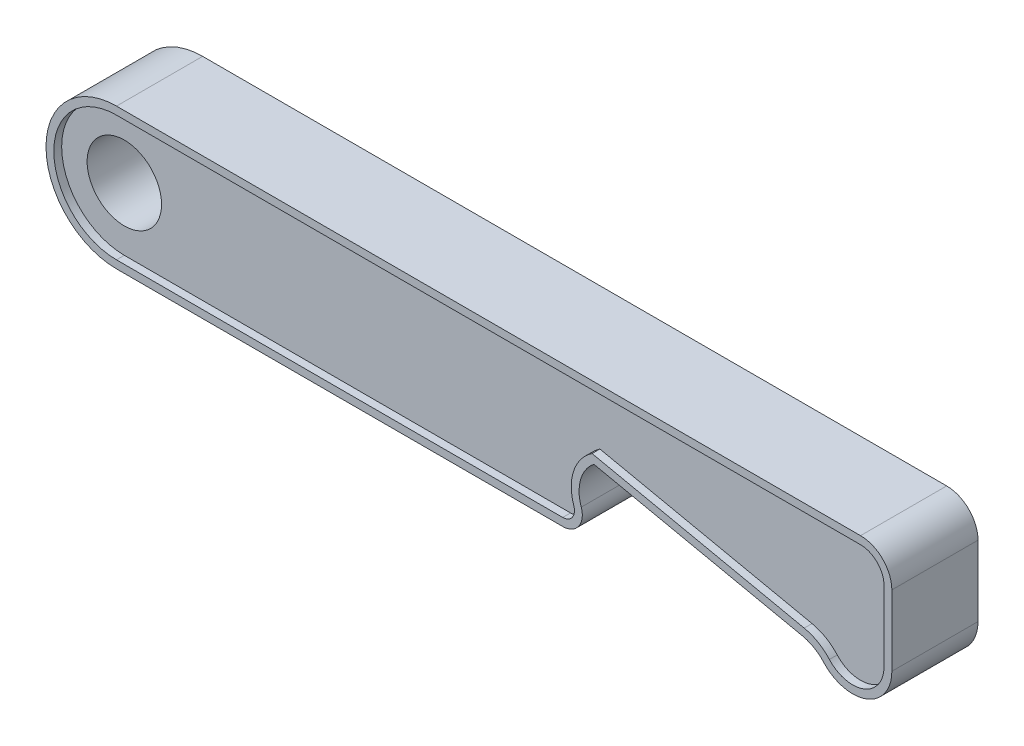
SolidWorks part; units mm, degrees
material "AISI 1015 Steel, Cold Drawn (SS)"
ref_plane "Front Plane" through (0, 0, 0) normal (0, 0, 1) x (1, 0, 0)
ref_plane "Top Plane" through (0, 0, 0) normal (0, 1, 0) x (1, 0, 0)
ref_plane "Right Plane" through (0, 0, 0) normal (1, 0, 0) x (0, 0, -1)
sketch "Sketch2" plane through (0, 0, 0) normal (0, 0, 1) x (1, 0, 0)
  line L0 (0, -9) -> (56.9788, -9)
  line L1 (0, 9) -> (95, 9)
  line L4 (99, -4) -> (99, 5)
  line L5 (60.9491, -0.1302) -> (87.6039, -5.7958)
  circle A0 centre (0, 0) radius 4.75
  arc A1 (0, 9) -> (0, -9) centre (0, 0) ccw
  arc A2 (56.9788, -9) -> (59.3406, -5.6804) centre (56.9788, -6.5) ccw
  arc A3 (59.3406, -5.6804) -> (60.9491, -0.1302) centre (64.0643, -4.0412) cw
  arc A4 (87.6039, -5.7958) -> (90.2822, -7.3433) centre (86.5643, -10.6866) cw
  arc A5 (90.2822, -7.3433) -> (99, -4) centre (94, -4) ccw
  arc A6 (95, 9) -> (99, 5) centre (95, 5) cw
  point P2 (-9, 0)
  point P20 (0, 0)
  point P21 (0, 0)
  dimension "D1" = 108
  dimension "D3" = 5
  dimension "D4" = 5
  dimension "D5" = 5
  dimension "D6" = 22.5
  dimension "D7" = 18
  dimension "D2" = 2.5
  dimension "D8" = 9.5
  dimension "D9" = 4
  dimension "D10" = 12
extrude "Boss-Extrude1" add sketch "Sketch2" along normal blind 11
sketch "Sketch4" plane through (0, 0, 11) normal (0, 0, 1) x (1, 0, 0)
  line L8 (60.7205, 0.9407) -> (87.8118, -4.8177)
  line L9 (98, -4) -> (98, 5)
  line L10 (95, 8) -> (0, 8)
  line L11 (0, -8) -> (56.9788, -8)
  line L12 (60.7205, 0.9407) -> (87.8118, -4.8177)
  line L13 (98, -4) -> (98, 5)
  line L14 (95, 8) -> (0, 8)
  line L15 (0, -8) -> (56.9788, -8)
  arc A12 (56.9788, -8) -> (58.3959, -6.0082) centre (56.9788, -6.5) ccw
  arc A13 (60.7205, 0.9407) -> (58.3959, -6.0082) centre (64.0643, -4.0412) ccw
  arc A14 (91.0257, -6.6746) -> (87.8118, -4.8177) centre (86.5643, -10.6866) ccw
  arc A15 (91.0257, -6.6746) -> (98, -4) centre (94, -4) ccw
  arc A16 (98, 5) -> (95, 8) centre (95, 5) ccw
  arc A17 (0, 8) -> (0, -8) centre (0, 0) ccw
  arc A18 (56.9788, -8) -> (58.3959, -6.0082) centre (56.9788, -6.5) ccw
  arc A19 (60.7205, 0.9407) -> (58.3959, -6.0082) centre (64.0643, -4.0412) ccw
  arc A20 (91.0257, -6.6746) -> (87.8118, -4.8177) centre (86.5643, -10.6866) ccw
  arc A21 (91.0257, -6.6746) -> (98, -4) centre (94, -4) ccw
  arc A22 (98, 5) -> (95, 8) centre (95, 5) ccw
  arc A23 (0, 8) -> (0, -8) centre (0, 0) ccw
  dimension "D1" = 1
extrude "Cut-Extrude1" cut sketch "Sketch4" against normal blind 1
equation "\"A\" = 108"
equation "\"B\" = 12"
equation "\"C\" = 1.5"
